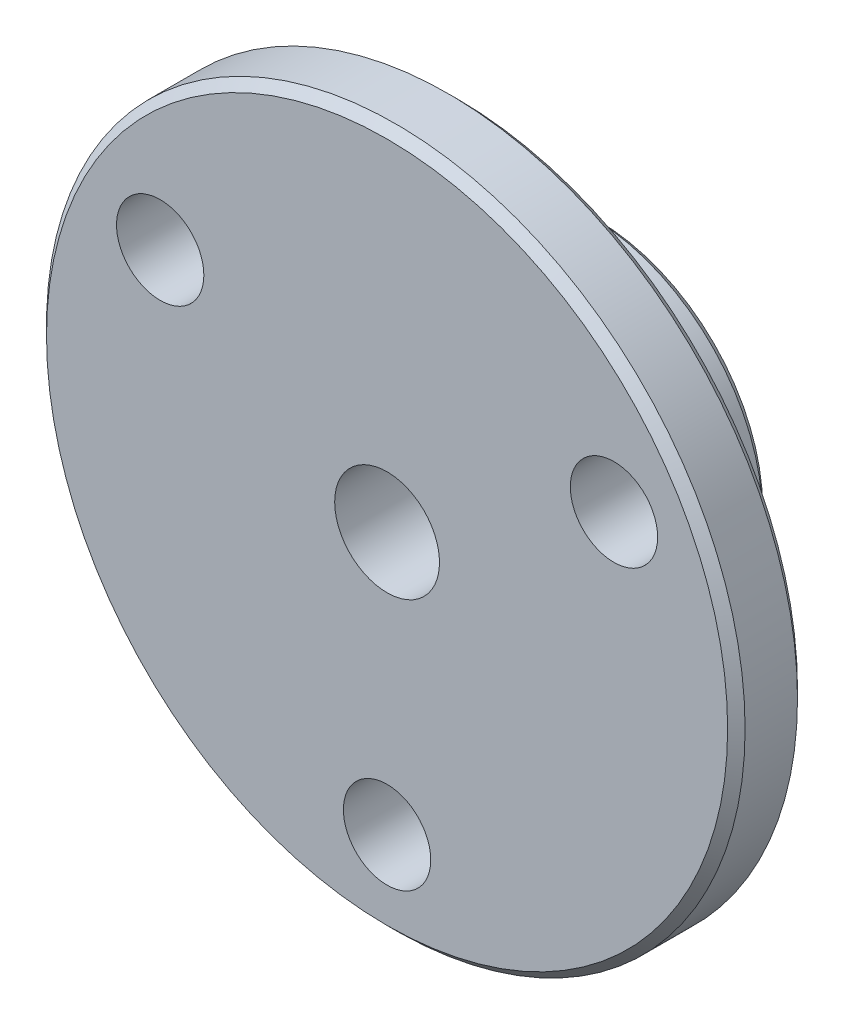
SolidWorks part; units mm, degrees
ref_plane "Front Plane" through (0, 0, 0) normal (0, 0, 1) x (1, 0, 0)
ref_plane "Top Plane" through (0, 0, 0) normal (0, 1, 0) x (1, 0, 0)
ref_plane "Right Plane" through (0, 0, 0) normal (1, 0, 0) x (0, 0, -1)
sketch "Sketch1" plane through (0, 0, 0) normal (0, 0, 1) x (1, 0, 0)
  circle A0 centre (0, 0) radius 5
  dimension "D1" = 10
extrude "Boss-Extrude1" add sketch "Sketch1" against normal blind 4
sketch "Sketch2" plane through (0, 0, 0) normal (0, 0, 1) x (1, 0, 0)
  line L0 (0, 7.5) -> (0, 0) construction
  line L1 (0, 0) -> (-6.4952, 3.75) construction
  line L2 (0, -7.5) -> (0, 0) construction
  line L3 (0, 0) -> (6.4952, 3.75) construction
  circle A0 centre (0, 0) radius 10
  circle A1 centre (0, 0) radius 7.5 construction
  circle A2 centre (-6.4952, 3.75) radius 1.25
  circle A3 centre (6.4952, 3.75) radius 1.25
  circle A4 centre (0, -7.5) radius 1.25
  point P9 (0, 0)
  point P13 (0, 0)
  dimension "D1" = 20
  dimension "D2" = 15
  dimension "D3" = 2.5
  dimension "D4" = 60
  dimension "D6" = 60
  dimension "D5" = 3
extrude "Boss-Extrude2" add sketch "Sketch2" along normal blind 2
sketch "Sketch3" plane through (0, 0, -4) normal (0, 0, -1) x (-1, 0, 0)
  circle A0 centre (0, 0) radius 1.5
  dimension "D1" = 3
extrude "Cut-Extrude1" cut sketch "Sketch3" against normal through all
chamfer "Chamfer1" distance 0.25 angle 45 4 edges at (10, 0, 2) (10, 0, 0) (5, 0, 0) (5, 0, -4)
